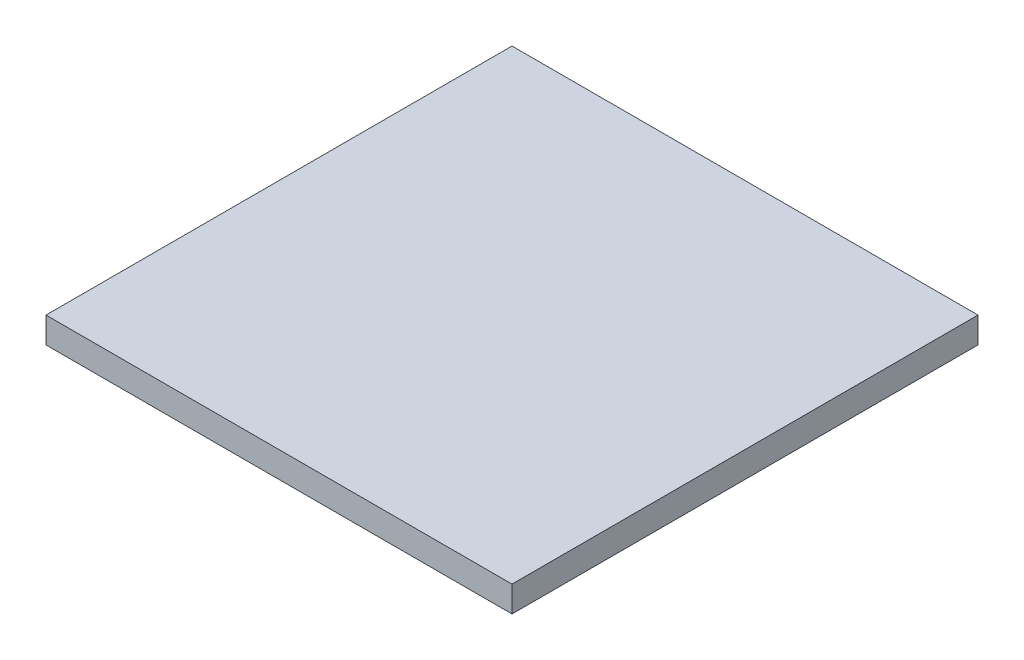
SolidWorks part; units mm, degrees
material "Pine"
ref_plane "Front Plane" through (0, 0, 0) normal (0, 0, 1) x (1, 0, 0)
ref_plane "Top Plane" through (0, 0, 0) normal (0, 1, 0) x (1, 0, 0)
ref_plane "Right Plane" through (0, 0, 0) normal (1, 0, 0) x (0, 0, -1)
sketch "Sketch1" plane through (0, 0, 0) normal (0, 0, 1) x (1, 0, 0)
  line L1 (0, 0) -> (-450, 0)
  line L2 (0, 0) -> (0, 25)
  line L3 (0, 25) -> (-450, 25)
  line L4 (-450, 0) -> (-450, 25)
  dimension "D1" = 25
  dimension "D2" = 450
extrude "Boss-Extrude1" add sketch "Sketch1" along normal blind 450
